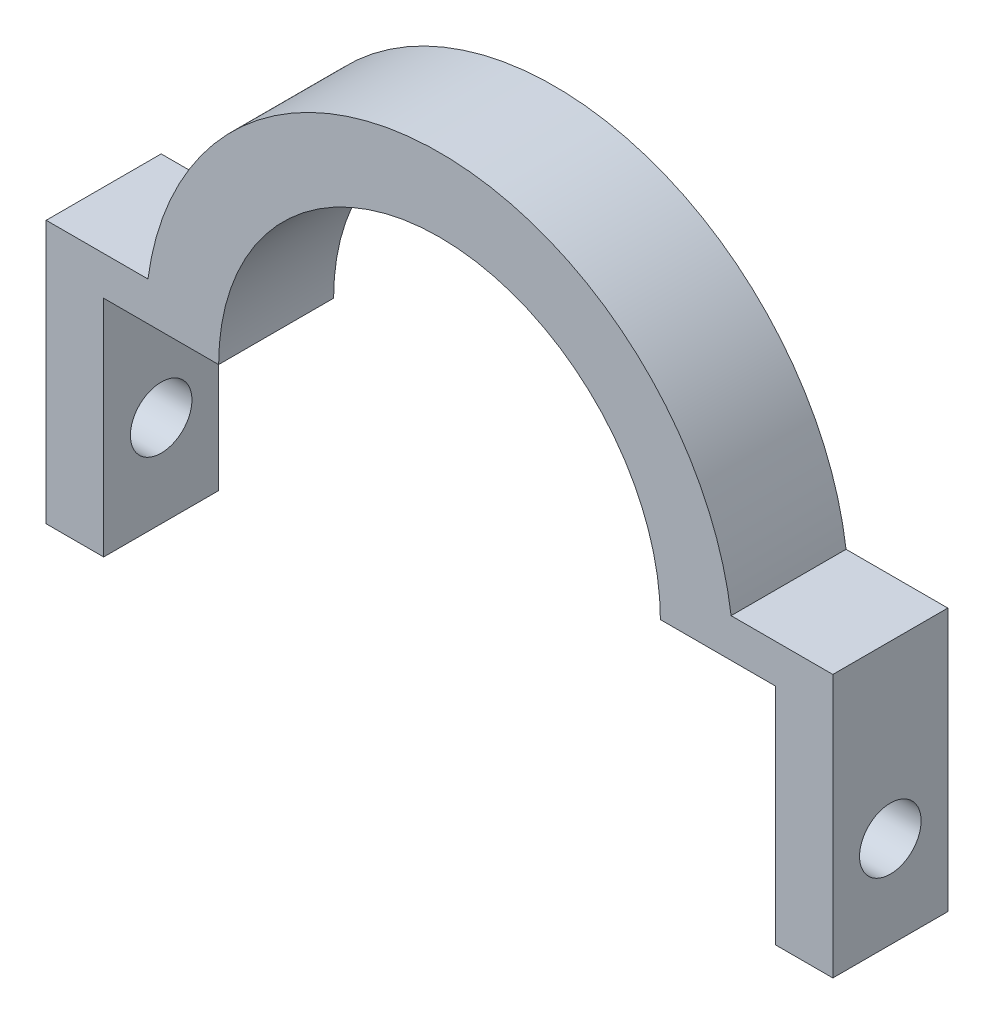
SolidWorks part; units mm, degrees
ref_plane "Front Plane" through (0, 0, 0) normal (0, 0, 1) x (1, 0, 0)
ref_plane "Top Plane" through (0, 0, 0) normal (0, 1, 0) x (1, 0, 0)
ref_plane "Right Plane" through (0, 0, 0) normal (1, 0, 0) x (0, 0, -1)
sketch "Sketch1" plane through (0, 0, 0) normal (0, 0, 1) x (1, 0, 0)
  line L10 (39.412, 14.521) -> (45.032, 14.521)
  line L17 (41.857, 12.38) -> (41.857, 0)
  line L18 (41.857, 0) -> (45.032, 0)
  line L25 (35.507, 12.38) -> (41.857, 12.38)
  line L26 (45.032, 14.521) -> (45.032, 0)
  line L27 (11.107, 12.38) -> (4.757, 12.38)
  line L28 (7.2019, 14.521) -> (1.582, 14.521)
  line L29 (1.582, 14.521) -> (1.582, 0)
  line L30 (4.757, 12.38) -> (4.757, 0)
  line L31 (4.757, 0) -> (1.582, 0)
  arc A0 (35.507, 12.38) -> (11.107, 12.38) centre (23.307, 12.38) ccw
  arc A1 (7.2019, 14.521) -> (39.412, 14.521) centre (23.307, 12.38) cw
  dimension "D1" = 24.4
  dimension "D8" = 16.2467
  dimension "D2" = 6.35
  dimension "D3" = 6.35
  dimension "D4" = 3.175
  dimension "D5" = 3.175
  dimension "D6" = 12.38
  dimension "D7" = 12.38
extrude "Boss-Extrude1" add sketch "Sketch1" along normal blind 6.35
sketch "Sketch2" plane through (45.032, 0, 0) normal (1, 0, 0) x (0, 0, -1)
  line L1 (-6.35, 0) -> (0, 0) construction
  circle A1 centre (-3.175, 5.08) radius 1.7
  point P5 (-3.175, 0)
  dimension "D1" = 3.4
  dimension "D3" = 5.08
  dimension "D2" = 0
extrude "Cut-Extrude1" cut sketch "Sketch2" against normal through all and the other way through all
